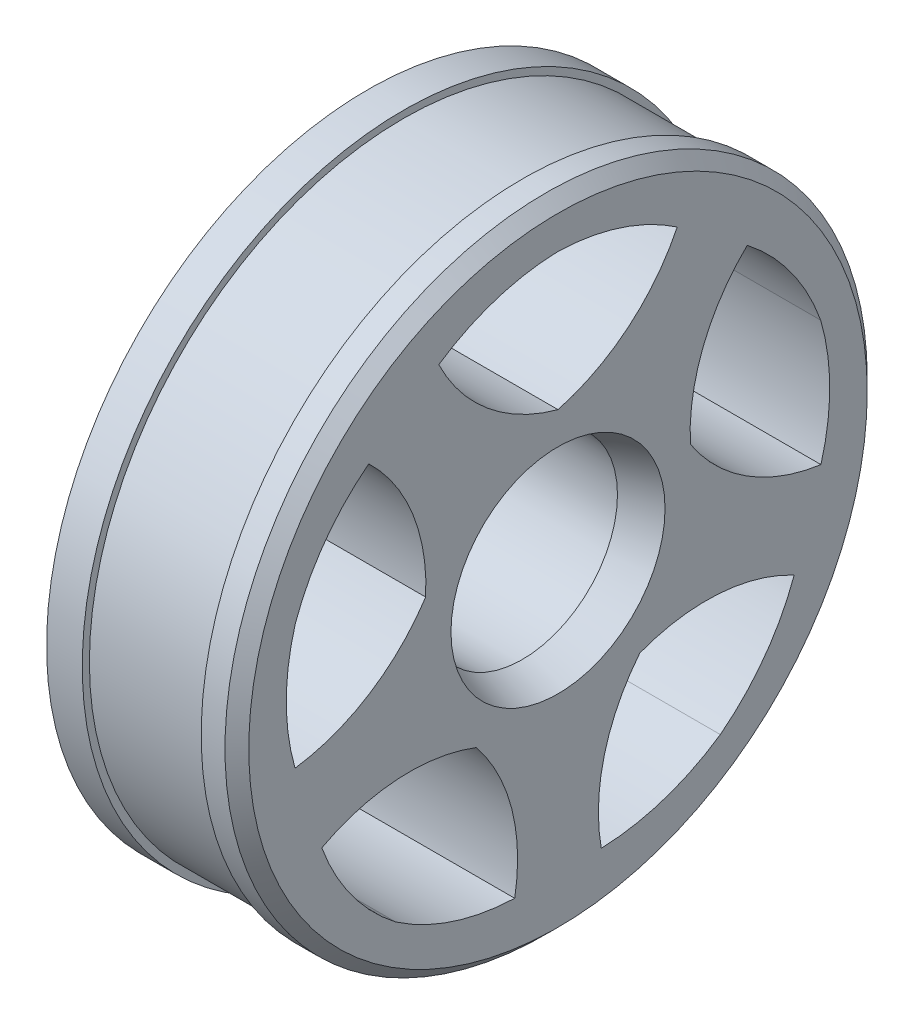
SolidWorks part; units mm, degrees
ref_plane "Front Plane" through (0, 0, 0) normal (0, 0, 1) x (1, 0, 0)
ref_plane "Top Plane" through (0, 0, 0) normal (0, 1, 0) x (1, 0, 0)
ref_plane "Right Plane" through (0, 0, 0) normal (1, 0, 0) x (0, 0, -1)
sketch "Sketch1" plane through (0, 0, 0) normal (1, 0, 0) x (0, 0, -1)
  circle A0 centre (0, 0) radius 13.5
  circle A1 centre (0, 0) radius 4
  dimension "D1" = 27
  dimension "D2" = 8
extrude "Boss-Extrude1" add sketch "Sketch1" along normal mid plane 8
sketch "Sketch2" plane through (0, 0, 0) normal (1, 0, 0) x (0, 0, -1)
  line L0 (0, 0) -> (0, 14.8201) construction
  arc A0 (0, 5.8497) -> (-5.0122, 9.994) centre (2.0377, 13.4173) cw
  arc A1 (-5.0122, 9.994) -> (0, 11.6087) centre (0.2591, 2.218) cw
  arc A2 (5.0122, 9.994) -> (0, 11.6087) centre (-0.2591, 2.218) ccw
  arc A3 (0, 5.8497) -> (5.0122, 9.994) centre (-2.0377, 13.4173) ccw
extrude "Cut-Extrude1" cut sketch "Sketch2" along normal through all both and the other way through all
pattern_circular "CirPattern1" count 5 over 360 about axis through (0, 0, 0) along (1, 0, 0) of "Cut-Extrude1"
chamfer "Chamfer1" distance 0.5 angle 45 1 edges at (4, 0, -13.5)
sketch "Sketch4" plane through (0, 0, 0) normal (1, 0, 0) x (0, 0, -1)
  circle A0 centre (0, 0) radius 13.5
  circle A1 centre (0, 0) radius 13.2
  circle A2 centre (0, 0) radius 13.5 construction
  dimension "D1" = 0.3
extrude "Cut-Extrude3" cut sketch "Sketch4" against normal mid plane 5
chamfer "Chamfer2" distance 0.5 distance2 1.5 1 edges at (4, 0, -4)
equation "\"axis_diameter\"=5.66"
equation "\"padding\"=0.5"
